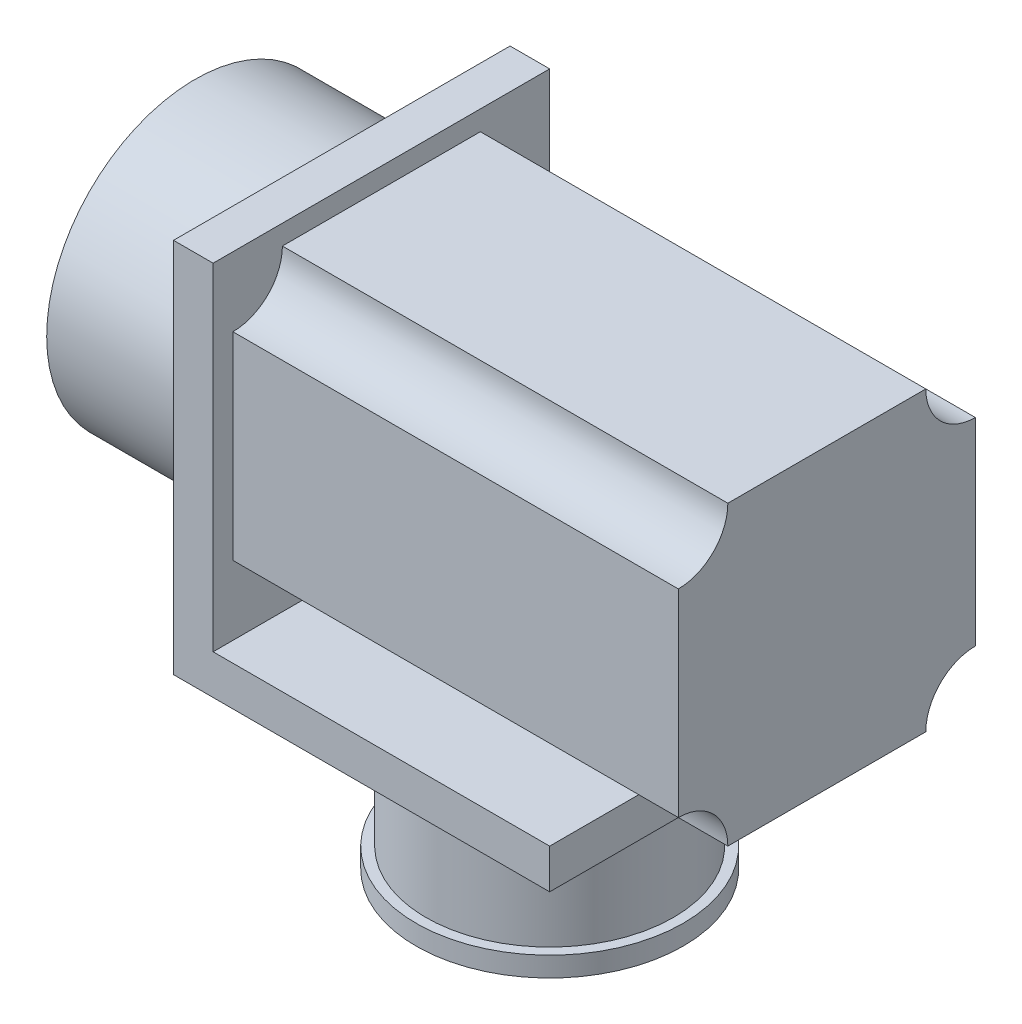
SolidWorks part; units mm, degrees
ref_plane "Front Plane" through (0, 0, 0) normal (0, 0, 1) x (1, 0, 0)
ref_plane "Top Plane" through (0, 0, 0) normal (0, 1, 0) x (1, 0, 0)
ref_plane "Right Plane" through (0, 0, 0) normal (1, 0, 0) x (0, 0, -1)
sketch "Sketch2" plane through (0, 0, 0) normal (0, 0, 1) x (1, 0, 0)
  line L0 (-40.3983, 30.2385) -> (-20.3983, 30.2385)
  line L11 (-20.3983, 30.2385) -> (-20.3983, -139.7615)
  line L12 (-20.3983, -139.7615) -> (149.6017, -139.7615)
  line L13 (149.6017, -139.7615) -> (149.6017, -159.7615)
  line L14 (149.6017, -159.7615) -> (-40.3983, -159.7615)
  line L15 (-40.3983, -159.7615) -> (-40.3983, 30.2385)
extrude "Boss-Extrude1" add sketch "Sketch2" against normal blind 170
sketch "Sketch3" plane through (-40.3983, 0, 0) normal (-1, 0, 0) x (0, 0, 1)
  circle A1 centre (-85.9385, -54.7615) radius 75
  circle A2 centre (-85.9385, -54.7615) radius 62.5
extrude "Boss-Extrude2" add sketch "Sketch3" along normal blind 75
sketch "Sketch4" plane through (-20.3983, 0, 0) normal (1, 0, 0) x (0, 0, -1)
  line L1 (10, 20.2385) -> (160, 20.2385)
  line L2 (10, 20.2385) -> (10, -129.7615)
  line L3 (10, -129.7615) -> (160, -129.7615)
  line L4 (160, 20.2385) -> (160, -129.7615)
extrude "Boss-Extrude3" add sketch "Sketch4" along normal blind 225
sketch "Sketch5" plane through (204.6017, 0, 0) normal (1, 0, 0) x (0, 0, -1)
  line L4 (10, 20.2385) -> (10, -129.7615)
  line L5 (10, -129.7615) -> (160, -129.7615)
  line L6 (160, -129.7615) -> (160, 20.2385)
  line L7 (160, 20.2385) -> (10, 20.2385)
  line L8 (10, 20.2385) -> (10, -129.7615)
  line L9 (10, -129.7615) -> (160, -129.7615)
  line L10 (160, -129.7615) -> (160, 20.2385)
  line L11 (160, 20.2385) -> (10, 20.2385)
  arc A4 (10, -4.7615) -> (35, 20.2385) centre (10, 20.2385) ccw
  arc A5 (135, 20.2385) -> (160, -4.7615) centre (160, 20.2385) ccw
  arc A6 (135, -129.7615) -> (160, -104.7615) centre (160, -129.7615) cw
  arc A7 (35, -129.7615) -> (10, -104.7615) centre (10, -129.7615) ccw
  line M1 (10, 20.2385) -> (10, -129.7615)
  line M2 (10, -129.7615) -> (160, -129.7615)
  line M3 (160, -129.7615) -> (160, 20.2385)
  line M4 (160, 20.2385) -> (10, 20.2385)
  dimension "D1" = 0
extrude "Cut-Extrude6" cut sketch "Sketch5" against normal up to surface (225 mm away) contours A4 L11 M1 | A7 M2 M1 | A6 L9 M3 | A5 L10 M4 up to face at (-20.3983, -54.7615, -85)
sketch "Sketch6" plane through (0, -159.7615, 0) normal (0, -1, 0) x (1, 0, 0)
  circle A0 centre (64.6017, -85) radius 62.5
extrude "Boss-Extrude4" add sketch "Sketch6" along normal blind 75
sketch "Sketch7" plane through (0, -234.7615, 0) normal (0, -1, 0) x (1, 0, 0)
  circle A0 centre (64.6017, -85) radius 67.5
  circle A1 centre (64.6017, -85) radius 62.5
  circle A2 centre (64.6017, -85) radius 62.5
  dimension "D2" = 5
  dimension "D1" = 0
extrude "Boss-Extrude5" add sketch "Sketch7" against normal blind 10
ref_axis "Axis1" through (-115.3983, -54.7615, -85.9385) along (1, 0, 0)
ref_plane "Plane1" through (0, -54.7615, 0) normal (0, -1, 0) x (1, 0, 0)
sketch "Sketch8" plane through (0, -54.7615, 0) normal (0, -1, 0) x (1, 0, 0)
  line L4 (-40.3983, -10.9385) -> (-40.3983, -160.9385) construction
  line L5 (-50.3983, -18.4385) -> (-40.3983, -18.4385)
  line L6 (-50.3983, -18.4385) -> (-50.3983, -30.8512)
  line L7 (-50.3983, -30.8512) -> (-40.3983, -30.8512)
  line L8 (-40.3983, -18.4385) -> (-40.3983, -30.8512)
  dimension "D1" = 10
revolve "Cut-Revolve1" cut sketch "Sketch8" angle 360 about axis through (-115.3983, -54.7615, -85.9385) along (1, 0, 0)
